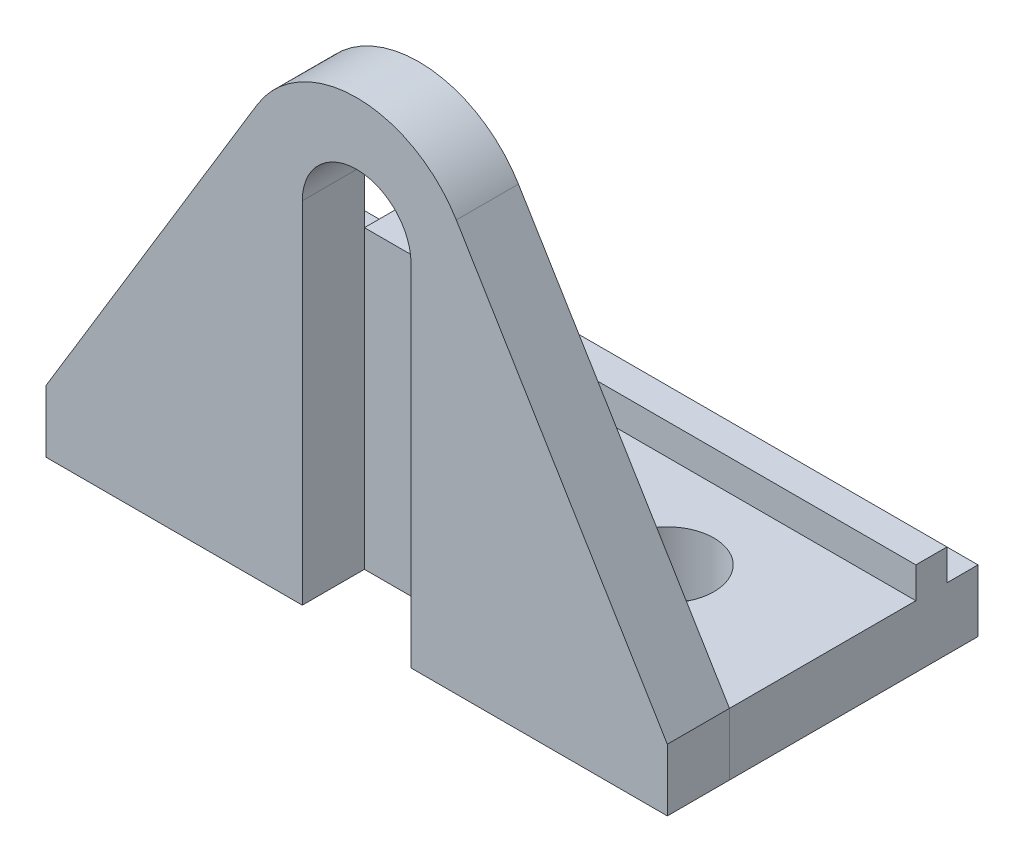
SolidWorks part; units mm, degrees
ref_plane "Front Plane" through (0, 0, 0) normal (0, 0, 1) x (1, 0, 0)
ref_plane "Top Plane" through (0, 0, 0) normal (0, 1, 0) x (1, 0, 0)
ref_plane "Right Plane" through (0, 0, 0) normal (1, 0, 0) x (0, 0, -1)
sketch "Sketch1" plane through (0, 0, 0) normal (0, 0, 1) x (1, 0, 0)
  line L0 (10.7232, 1) -> (3.931, 12.2176)
  line L2 (-9.2768, 1) -> (-9.2768, -1)
  line L3 (-9.2768, -1) -> (10.7232, -1)
  line L4 (10.7232, 1) -> (10.7232, -1)
  line L5 (-1.0268, 10.2753) -> (-1.0268, -1)
  line L6 (2.4732, 10.2753) -> (2.4732, -1)
  line L11 (-9.2768, 1) -> (-2.4846, 12.2176)
  arc A1 (2.4732, 10.2753) -> (-1.0268, 10.2753) centre (0.7232, 10.2753) ccw
  arc A2 (3.931, 12.2176) -> (-2.4846, 12.2176) centre (0.7232, 10.2753) ccw
  point P0 (0, 0)
  point P6 (0.7232, 12.0253)
  dimension "D3" = 1.75
  dimension "D4" = 2
  dimension "D1" = 20
  dimension "D2" = 2
  dimension "D5" = 8.25
extrude "Boss-Extrude1" add sketch "Sketch1" along normal blind 2 contours L0 A2 L11 L2 L3 L5 A1 L6 L4
sketch "Sketch2" plane through (0, 0, 0) normal (0, 0, -1) x (-1, 0, 0)
  line L0 (1.0268, 10.2753) -> (1.0268, -1) construction
  line L1 (-10.7232, -1) -> (9.2768, -1)
  line L2 (9.2768, -1) -> (9.2768, 1)
  line L3 (9.2768, 1) -> (1.0268, 1)
  line L4 (-2.4732, 1) -> (-10.7232, 1)
  line L5 (-10.7232, 1) -> (-10.7232, -1)
  line L6 (-2.4732, 1) -> (-2.4732, 8.525)
  line L7 (-2.4732, 8.525) -> (1.0268, 8.525)
  line L8 (1.0268, 1) -> (1.0268, 8.525)
  dimension "D1" = 3.5
  dimension "D2" = 7.525
extrude "Boss-Extrude4" add sketch "Sketch2" along normal blind 2 separate body
sketch "Sketch4" plane through (0, 0, -2) normal (0, 0, -1) x (-1, 0, 0)
  line L1 (-10.7232, 1) -> (9.2768, 1)
  line L2 (-10.7232, 1) -> (-10.7232, -1)
  line L3 (-10.7232, -1) -> (9.2768, -1)
  line L4 (9.2768, 1) -> (9.2768, -1)
extrude "Boss-Extrude5" add sketch "Sketch4" along normal blind 6
sketch "Sketch5" plane through (0, 1, 0) normal (0, 1, 0) x (1, 0, 0)
  line L0 (-9.2768, 8) -> (-9.2768, 0) construction
  line L1 (-9.2768, 7) -> (10.7232, 7)
  line L2 (-9.2768, 7) -> (-9.2768, 6)
  line L3 (-9.2768, 6) -> (10.7232, 6)
  line L4 (10.7232, 7) -> (10.7232, 6)
  line L5 (10.7232, 8) -> (10.7232, 0) construction
  line L6 (-9.2768, 8) -> (10.7232, 8) construction
  dimension "D1" = 1
  dimension "D2" = 1
extrude "Boss-Extrude6" add sketch "Sketch5" along normal blind 1
sketch "Sketch6" plane through (0, 1, 0) normal (0, 1, 0) x (1, 0, 0)
  line L0 (-1.0268, 2) -> (2.4732, 2) construction
  line L1 (2.4732, 0) -> (10.7232, 0) construction
  line L2 (-9.2768, 0) -> (-1.0268, 0) construction
  line L4 (10.7232, 6) -> (10.7232, 0) construction
  line L5 (-9.2768, 6) -> (-9.2768, 0) construction
  circle A0 centre (5.7232, 3) radius 1.5
  circle A1 centre (-4.2768, 3) radius 1.5
  point P0 (0.7232, 2)
  point P9 (-9.2768, 3)
  dimension "D1" = 3
  dimension "D2" = 3
  dimension "D3" = 5
  dimension "D4" = 5
extrude "Cut-Extrude2" cut sketch "Sketch6" against normal up to surface (2 mm away) up to face at (0.7232, -1, -4)
sketch "Sketch8" plane through (0, 0, 0) normal (0, 0, -1) x (-1, 0, 0)
  point P0 (-0.7326, 12.3007)
